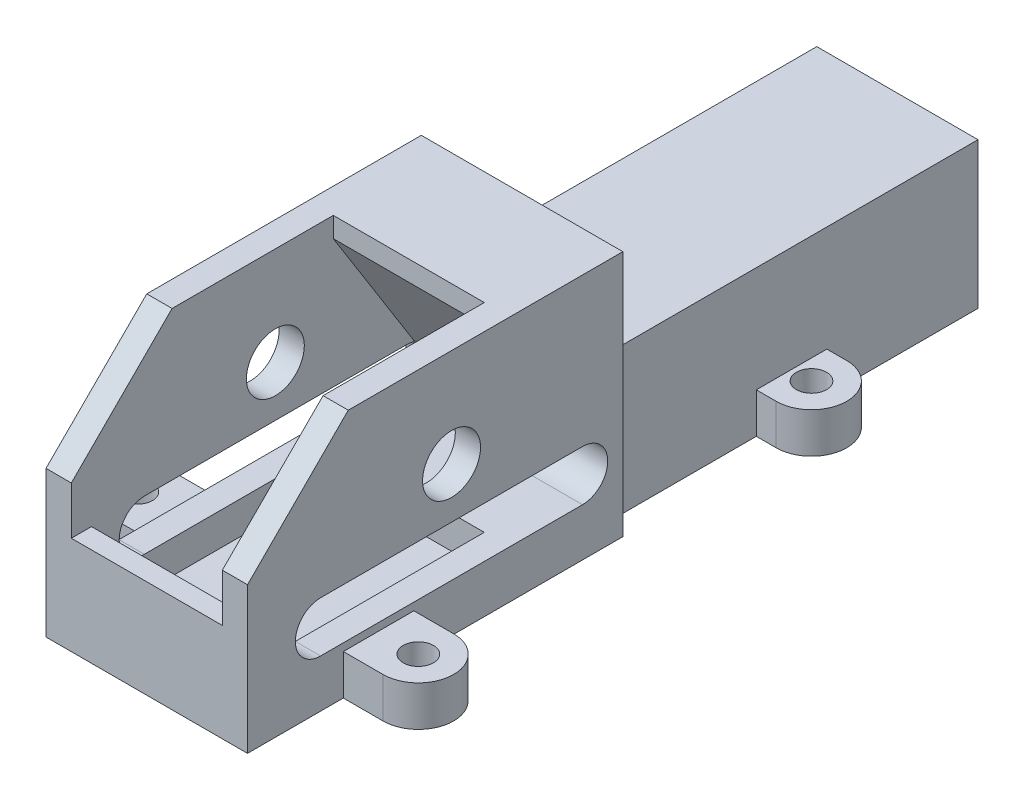
SolidWorks part; units mm, degrees
material "6063-T5"
ref_plane "Front Plane" through (0, 0, 0) normal (0, 0, 1) x (1, 0, 0)
ref_plane "Top Plane" through (0, 0, 0) normal (0, 1, 0) x (1, 0, 0)
ref_plane "Right Plane" through (0, 0, 0) normal (1, 0, 0) x (0, 0, -1)
sketch "Sketch1" plane through (0, 0, 0) normal (0, 1, 0) x (1, 0, 0)
  line L0 (-8, -37.25) -> (8, -37.25)
  line L1 (-8, -37.25) -> (-8, 37.25)
  line L2 (8, -37.25) -> (8, 37.25)
  line L3 (-8, 37.25) -> (8, 37.25)
  line L4 (-8, -37.25) -> (8, 37.25) construction
  line L5 (8, -37.25) -> (-8, 37.25) construction
  point P1 (0, 0)
  dimension "D1" = 16
  dimension "D2" = 74.5
extrude "Boss-Extrude1" add sketch "Sketch1" along normal blind 14.5
sketch "Sketch2" plane through (0, 0, 0) normal (0, -1, 0) x (-1, 0, 0)
  line L0 (0, 37.25) -> (0, 18.75)
  line L1 (-8, 37.25) -> (8, 37.25) construction
  line L2 (0, 18.75) -> (9.975, 18.75)
  line L3 (9.975, 22.25) -> (8, 22.25)
  line L4 (8, 37.25) -> (8, -37.25) construction
  line L5 (9.975, 15.25) -> (8, 15.25)
  line L6 (8, 22.25) -> (8, 15.25)
  circle A0 centre (9.975, 18.75) radius 1.5
  circle A1 centre (9.975, 18.75) radius 3.5
  dimension "D3" = 3
  dimension "D4" = 7
  dimension "D1" = 18.5
  dimension "D2" = 9.975
extrude "Boss-Extrude2" add sketch "Sketch2" against normal blind 4
mirror "Mirror1" about plane through (0, 0, 0) normal (1, 0, 0) of "Boss-Extrude2"
sketch "Sketch3" plane through (0, 0, 0) normal (0, -1, 0) x (-1, 0, 0)
  line L0 (0, 0) -> (10, 0)
  line L1 (0, -37.25) -> (-10, -37.25)
  line L2 (8, -37.25) -> (-8, -37.25) construction
  line L4 (-10, -37.25) -> (10, -37.25)
  line L5 (-10, -37.25) -> (-10, 0)
  line L6 (-10, 0) -> (10, 0)
  line L7 (10, -37.25) -> (10, 0)
  line M13 (-8, 15.25) -> (-8, -37.25)
  line M15 (8, -37.25) -> (8, 15.25)
  dimension "D1" = 10
  dimension "D2" = 10
extrude "Boss-Extrude3" add sketch "Sketch3" against normal up to surface (14.5 mm away) contours L4 L7 L0 M15 | L6 L5 L1 M13 up to face at (0, 14.5, 0)
sketch "Sketch4" plane through (0, 0, 0) normal (0, -1, 0) x (-1, 0, 0)
  line L0 (9.975, 18.75) -> (-9.975, 18.75)
  line L1 (0, 18.75) -> (0, -24.24)
  line L2 (0, -24.24) -> (13.945, -24.24)
  line L3 (13.945, -20.74) -> (10, -20.74)
  line L5 (10, -37.25) -> (10, 0) construction
  line L6 (13.945, -27.74) -> (10, -27.74)
  line L7 (10, -27.74) -> (10, -20.74)
  circle A0 centre (13.945, -24.24) radius 1.5
  circle A1 centre (13.945, -24.24) radius 3.5
  dimension "D3" = 3
  dimension "D4" = 7
  dimension "D1" = 42.99
  dimension "D2" = 13.945
extrude "Boss-Extrude4" add sketch "Sketch4" against normal blind 4
mirror "Mirror4" about plane through (0, 0, 0) normal (1, 0, 0) of "Boss-Extrude4"
sketch "Sketch5" plane through (10, 0, 0) normal (1, 0, 0) x (0, 0, -1)
  line L0 (-37.25, 7.25) -> (-30, 7.25)
  line L1 (-37.25, 14.5) -> (-37.25, 0) construction
  line L2 (-30, 7.25) -> (-4, 7.25)
  line L3 (-4, 4.75) -> (-30, 4.75)
  line L4 (-4, 9.75) -> (-30, 9.75)
  circle A0 centre (-30, 7.25) radius 2.5
  circle A1 centre (-4, 7.25) radius 2.5
  dimension "D2" = 5
  dimension "D4" = 5
  dimension "D1" = 7.25
  dimension "D3" = 26
  dimension "D5" = 26
  dimension "D6" = 26
extrude "Cut-Extrude1" cut sketch "Sketch5" against normal through all contours A1 L2 A0 L3 | A1 L4 A0 L2
sketch "Sketch7" plane through (0, 14.5, 0) normal (0, 1, 0) x (1, 0, 0)
  line L1 (10, 0) -> (-10, 0)
  line L2 (10, 0) -> (10, -37.25)
  line L3 (10, -37.25) -> (-10, -37.25)
  line L4 (-10, 0) -> (-10, -37.25)
extrude "Boss-Extrude5" add sketch "Sketch7" along normal blind 10
sketch "Sketch8" plane through (0, 24.5, 0) normal (0, 1, 0) x (1, 0, 0)
  line L0 (0, -37.25) -> (0, -11.25)
  line L1 (-10, -37.25) -> (10, -37.25) construction
  line L2 (0, -11.25) -> (7.5, -11.25)
  line L3 (-7.4866, -37.25) -> (-7.4866, -11.25)
  line L4 (-7.4866, -37.25) -> (7.5, -37.25)
  line L5 (-7.4866, -11.25) -> (7.5, -11.25)
  line L6 (7.5, -37.25) -> (7.5, -11.25)
  line L7 (-7.4866, -37.25) -> (7.5, -11.25) construction
  line L8 (-7.4866, -11.25) -> (7.5, -37.25) construction
  point P7 (0.0067, -24.25)
  line M7 (-10, -37.25) -> (10, -37.25)
  dimension "D1" = 26
  dimension "D2" = 7.5
  dimension "D3" = 26
extrude "Cut-Extrude2" cut sketch "Sketch8" against normal blind 23 contours L6 L2 L0 M7 | L5 L3 L0 M7
sketch "Sketch10" plane through (0, 1.5, 0) normal (0, 1, 0) x (1, 0, 0)
  line L0 (7.5, -37.25) -> (7.5, -35.25)
  line L1 (7.5, -37.25) -> (7.5, -11.25) construction
  line L3 (7.5, -35.25) -> (-7.4866, -35.25)
  line L4 (7.5, -35.25) -> (7.5, -37.25)
  line L5 (7.5, -37.25) -> (-7.4866, -37.25)
  line L6 (-7.4866, -35.25) -> (-7.4866, -37.25)
  line M2 (-7.4866, -37.25) -> (7.5, -37.25)
  line M3 (7.5, -37.25) -> (7.5, -11.25)
  line M5 (-7.4866, -11.25) -> (-7.4866, -37.25)
  dimension "D1" = 2
extrude "Boss-Extrude6" add sketch "Sketch10" along normal up to surface (13 mm away) contours L3 M3 M5 M2 up to face at (0, 14.5, -18.625)
sketch "Sketch12" plane through (7.5, 0, 0) normal (-1, 0, 0) x (0, 0, 1)
  line L0 (11.25, 24.5) -> (11.25, 22.5)
  line L1 (11.25, 9.75) -> (11.25, 24.5) construction
  line L2 (11.25, 22.5) -> (11.25, 9.75)
  line L3 (11.25, 9.75) -> (3.25, 9.75)
  line L5 (3.25, 9.75) -> (11.25, 22.5)
  line M8 (11.25, 24.5) -> (11.25, 9.75)
  dimension "D1" = 2
  dimension "D2" = 8
extrude "Cut-Extrude3" cut sketch "Sketch12" along normal up to surface (14.9866 mm away) contours L5 L3 M8 up to face at (-7.4866, 11, 25.25)
sketch "Sketch13" plane through (0, 9.75, 0) normal (0, 1, 0) x (1, 0, 0)
  line L1 (7.5, -3.25) -> (-7.4866, -3.25)
  line L2 (7.5, -3.25) -> (7.5, -4)
  line L3 (7.5, -4) -> (-7.4866, -4)
  line L4 (-7.4866, -3.25) -> (-7.4866, -4)
extrude "Cut-Extrude4" cut sketch "Sketch13" against normal blind 1
sketch "Sketch14" plane through (10, 0, 0) normal (1, 0, 0) x (0, 0, -1)
  line L0 (-1.5, 7.25) -> (-32.5, 7.25)
  line L1 (-17, 7.25) -> (-17, 14.75)
  arc A0 (-4, 4.75) -> (-4, 9.75) centre (-4, 7.25) ccw construction
  arc A1 (-30, 9.75) -> (-30, 4.75) centre (-30, 7.25) ccw construction
  circle A2 centre (-17, 14.75) radius 2.875
  dimension "D2" = 5.75
  dimension "D1" = 7.5
extrude "Cut-Extrude5" cut sketch "Sketch14" against normal through all
sketch "Sketch15" plane through (7.5, 0, 0) normal (-1, 0, 0) x (0, 0, 1)
  line L0 (37.25, 14.5) -> (37.25, 24.5)
  line L1 (37.25, 24.5) -> (27.25, 24.5)
  line L2 (37.25, 24.5) -> (11.25, 24.5) construction
  line L3 (27.25, 24.5) -> (37.25, 14.5)
  dimension "D1" = 10
extrude "Cut-Extrude6" cut sketch "Sketch15" along normal through all and the other way through all
ref_plane "Plane1" through (0, 7.25, 0) normal (0, 1, 0) x (1, 0, 0)
sketch "Sketch16" plane through (0, 14.5, 0) normal (0, 1, 0) x (1, 0, 0)
  line L1 (7.5, -35.25) -> (-7.4866, -35.25)
  line L2 (7.5, -35.25) -> (7.5, -37.25)
  line L3 (7.5, -37.25) -> (-7.4866, -37.25)
  line L4 (-7.4866, -35.25) -> (-7.4866, -37.25)
extrude "Cut-Extrude7" cut sketch "Sketch16" against normal up to surface (4.75 mm away) up to face at (8.75, 9.75, 17)
ref_plane "Plane2" through (0, 0, 17) normal (0, 0, 1) x (1, 0, 0)
